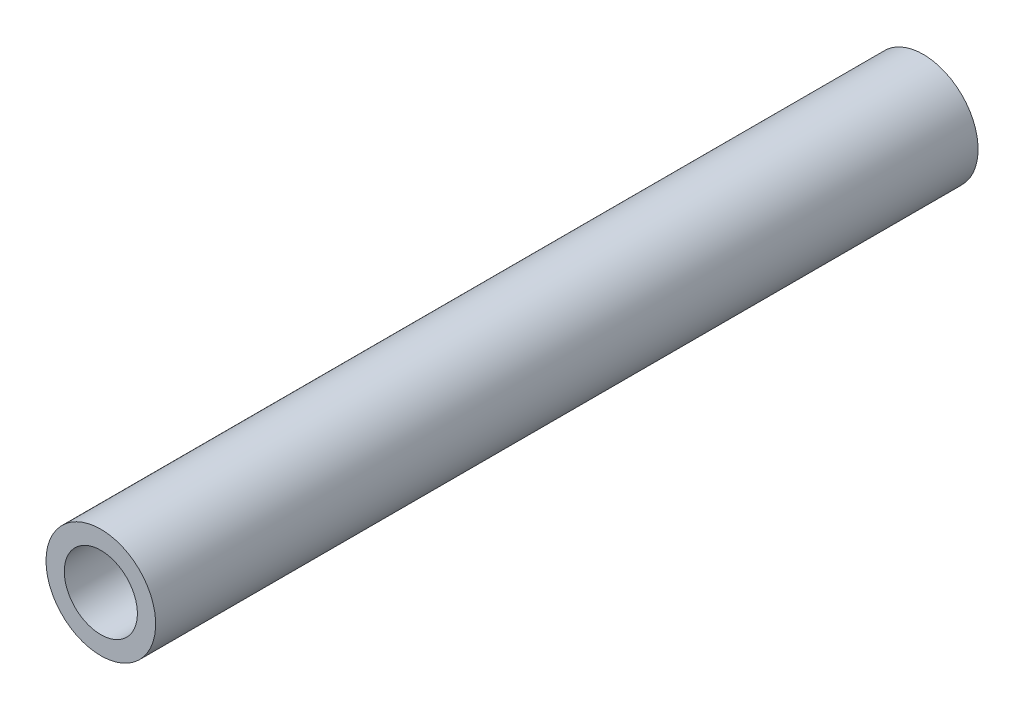
SolidWorks part; units mm, degrees
material "C-Fibra di vetro"
ref_plane "Piano frontale" through (0, 0, 0) normal (0, 0, 1) x (1, 0, 0)
ref_plane "Piano superiore" through (0, 0, 0) normal (0, 1, 0) x (1, 0, 0)
ref_plane "Piano destro" through (0, 0, 0) normal (1, 0, 0) x (0, 0, -1)
sketch "Schizzo1" plane through (0, 0, 0) normal (0, 0, 1) x (1, 0, 0)
  circle A0 centre (70, -82.5) radius 3
  circle A1 centre (70, -82.5) radius 2
  dimension "D1" = 6
  dimension "D2" = 1
extrude "Estrusione-Estrusione1" add sketch "Schizzo1" along normal up to surface (45 mm away)
